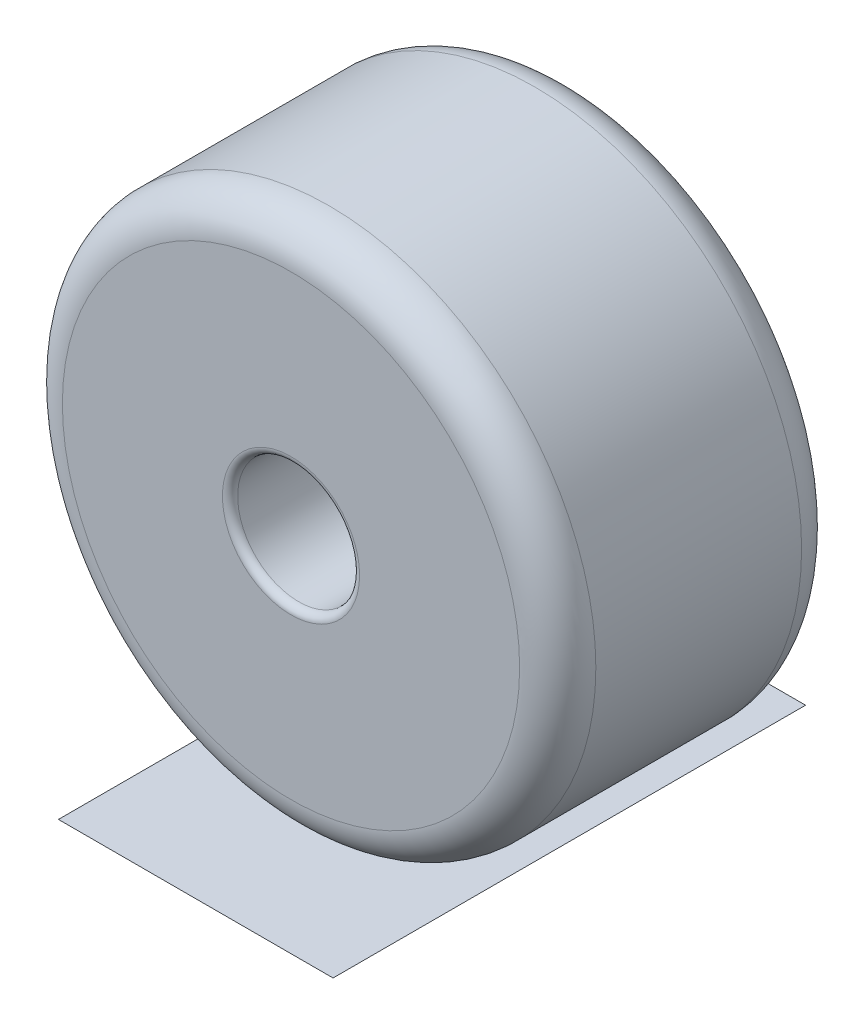
SolidWorks part; units mm, degrees
ref_plane "前视基准面" through (0, 0, 0) normal (0, 0, 1) x (1, 0, 0)
ref_plane "上视基准面" through (0, 0, 0) normal (0, 1, 0) x (1, 0, 0)
ref_plane "右视基准面" through (0, 0, 0) normal (1, 0, 0) x (0, 0, -1)
sketch "草图1" plane through (0, 0, 0) normal (0, 0, 1) x (1, 0, 0)
  circle A0 centre (0, 0) radius 17.5
  circle A1 centre (0, 0) radius 4
  dimension "D1" = 35
  dimension "D2" = 8
extrude "凸台-拉伸1" add sketch "草图1" along normal mid plane 18.5
fillet "圆角1" radius 2.5 2 edges at (17.5, 0, -9.25) (17.5, 0, 9.25)
fillet "圆角2" radius 0.5 2 edges at (4, 0, -9.25) (4, 0, 9.25)
sketch "草图2" plane through (0, 0, 0) normal (0, 0, 1) x (1, 0, 0)
  line L0 (-9.0097, -17.5) -> (9.0097, -17.5)
  circle A1 centre (0, 0) radius 17.5 construction
  point P3 (0, -17.5)
surface "曲面-拉伸3" sketch "草图2" parameters "D1"=31
equation "\"n\"=2.5"
